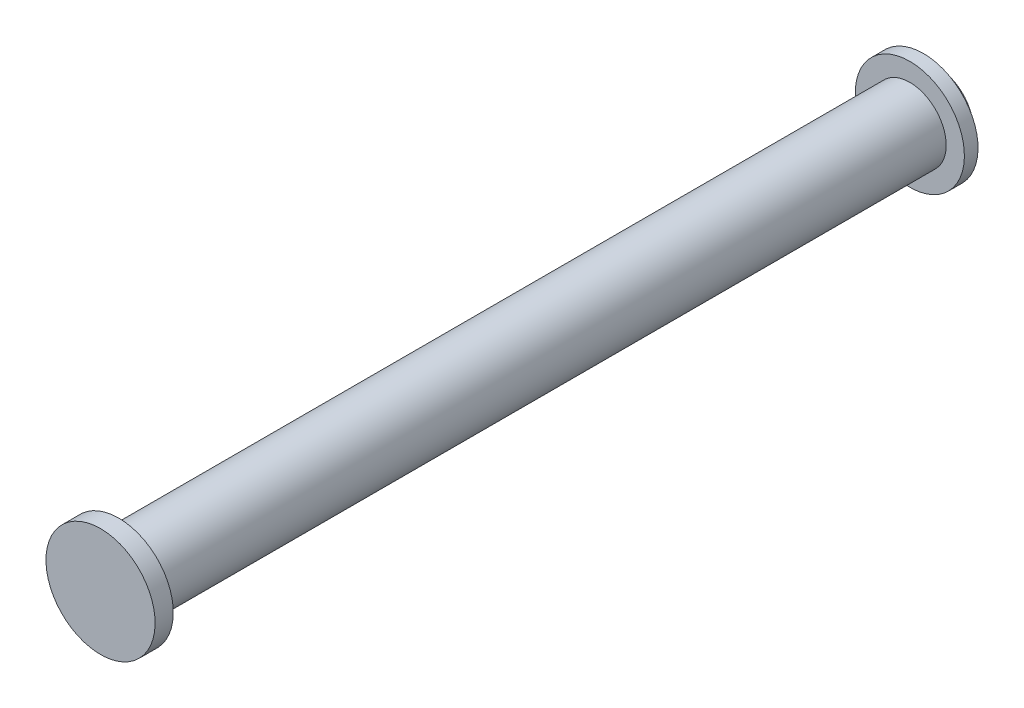
SolidWorks part; units mm, degrees
ref_plane "Front Plane" through (0, 0, 0) normal (0, 0, 1) x (1, 0, 0)
ref_plane "Top Plane" through (0, 0, 0) normal (0, 1, 0) x (1, 0, 0)
ref_plane "Right Plane" through (0, 0, 0) normal (1, 0, 0) x (0, 0, -1)
sketch "Sketch1" plane through (0, 0, 0) normal (1, 0, 0) x (0, 0, -1)
  line L0 (0, 0) -> (0, 6)
  line L1 (0, 6) -> (2, 6)
  line L2 (2, 6) -> (2, 4)
  line L3 (2, 4) -> (89, 4)
  line L4 (89, 4) -> (89, 6)
  line L5 (89, 6) -> (90.5, 6)
  line L6 (90.5, 6) -> (90.5, 4)
  line L7 (90.5, 4) -> (92, 4)
  line L8 (92, 4) -> (92, 0)
  line L9 (92, 0) -> (0, 0) construction
  line L10 (0, 0) -> (92, 0)
  dimension "D1" = 90
  dimension "D2" = 3
  dimension "D3" = 1.5
  dimension "D4" = 6
  dimension "D5" = 2
  dimension "D6" = 4
revolve "Revolve1" add sketch "Sketch1" angle 360 about L9
